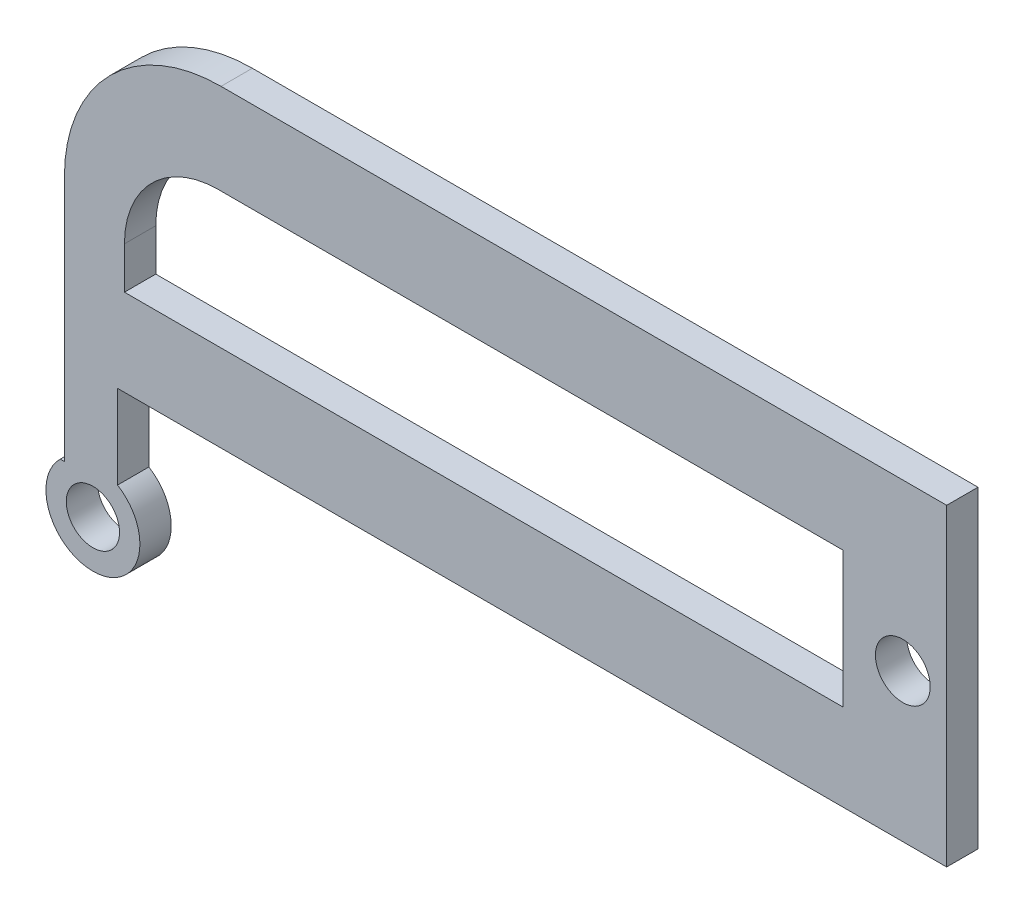
SolidWorks part; units mm, degrees
ref_plane "Front Plane" through (0, 0, 0) normal (0, 0, 1) x (1, 0, 0)
ref_plane "Top Plane" through (0, 0, 0) normal (0, 1, 0) x (1, 0, 0)
ref_plane "Right Plane" through (0, 0, 0) normal (1, 0, 0) x (0, 0, -1)
sketch "Sketch1" plane through (0, 0, 0) normal (0, 0, 1) x (1, 0, 0)
  line L0 (-24.3014, -6.7426) -> (21.4882, -6.7426)
  line L1 (-17.8401, 13.2574) -> (21.4882, 13.2574)
  line L2 (-24.3014, -6.7426) -> (21.4882, 13.2574) construction
  line L3 (-17.8401, 13.2574) -> (21.4882, -6.7426) construction
  line L4 (21.4882, -6.7426) -> (28.6306, -6.7426)
  line L5 (28.6306, -6.7426) -> (28.6306, 13.2574)
  line L6 (-17.8401, 13.2574) -> (-21.0053, 13.2574)
  line L7 (-24.3014, -6.7426) -> (-24.3014, -8.9941)
  line L8 (-27.6973, 13.2574) -> (-27.6973, -12.4867)
  line L10 (-20.6306, 21.008) -> (-20.6492, 20.6221)
  line L11 (-27.6973, -12.4867) -> (-27.9607, -12.4867)
  line L12 (-24.3014, -8.9941) -> (-24.3014, -12.0905)
  line L13 (21.4882, 13.2574) -> (28.6306, 13.2574)
  line L14 (-21.0053, 13.2574) -> (-27.6973, 13.2574)
  arc A0 (-20.6492, 20.6221) -> (-20.6306, 21.008) centre (-24.6306, 21.008) ccw
  arc A2 (-27.9607, -12.4867) -> (-24.3014, -12.0905) centre (-25.876, -14.6441) ccw
  circle A3 centre (-25.876, -14.6441) radius 1.7
  circle A4 centre (25.8308, 2.7003) radius 1.75
  point P0 (0.3314, 4.0165)
  dimension "D3" = 3
  dimension "D4" = 3.4
  dimension "D5" = 3.5
  dimension "D1" = 39.3283
  dimension "D2" = 20
extrude "Boss-Extrude2" add sketch "Sketch1" along normal blind 2
fillet "Fillet1" radius 10 1 edges at (-27.6973, 13.2574, 1)
sketch "Sketch2" plane through (0, 0, 2) normal (0, 0, 1) x (1, 0, 0)
  line L1 (-23.863, -1.2066) -> (22.0053, -1.2066)
  line L2 (-23.863, -1.2066) -> (-23.863, 1.4675)
  line L3 (-17.863, 7.4675) -> (22.0053, 7.4675)
  line L4 (22.0053, -1.2066) -> (22.0053, 7.4675)
  line L5 (-23.863, -1.2066) -> (22.0053, 7.4675) construction
  line L6 (-23.863, 7.4675) -> (22.0053, -1.2066) construction
  arc A0 (-23.863, 1.4675) -> (-17.863, 7.4675) centre (-17.863, 1.4675) cw
  point P0 (-0.9288, 3.1305)
  dimension "D1" = 6
extrude "Cut-Extrude1" cut sketch "Sketch2" against normal blind 4.3
